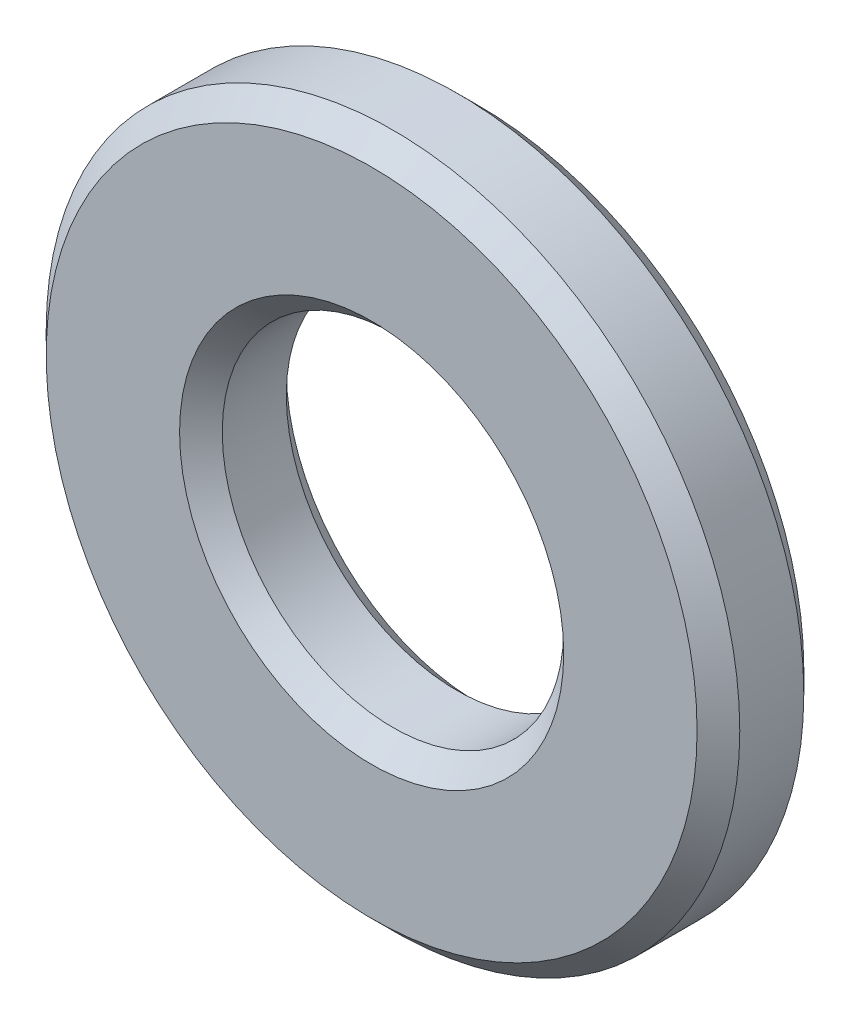
SolidWorks part; units mm, degrees
ref_plane "前视基准面" through (0, 0, 0) normal (0, 0, 1) x (1, 0, 0)
ref_plane "上视基准面" through (0, 0, 0) normal (0, 1, 0) x (1, 0, 0)
ref_plane "右视基准面" through (0, 0, 0) normal (1, 0, 0) x (0, 0, -1)
sketch "草图1" plane through (0, 0, 0) normal (0, 0, 1) x (1, 0, 0)
  circle A0 centre (0, 0) radius 16
  circle A1 centre (0, 0) radius 32.5
  dimension "D1" = 65
  dimension "D2" = 32
extrude "凸台-拉伸1" add sketch "草图1" along normal blind 10
chamfer "倒角1" distance 2 angle 45 4 edges at (16, 0, 0) (32.5, 0, 0) (16, 0, 10) (32.5, 0, 10)
